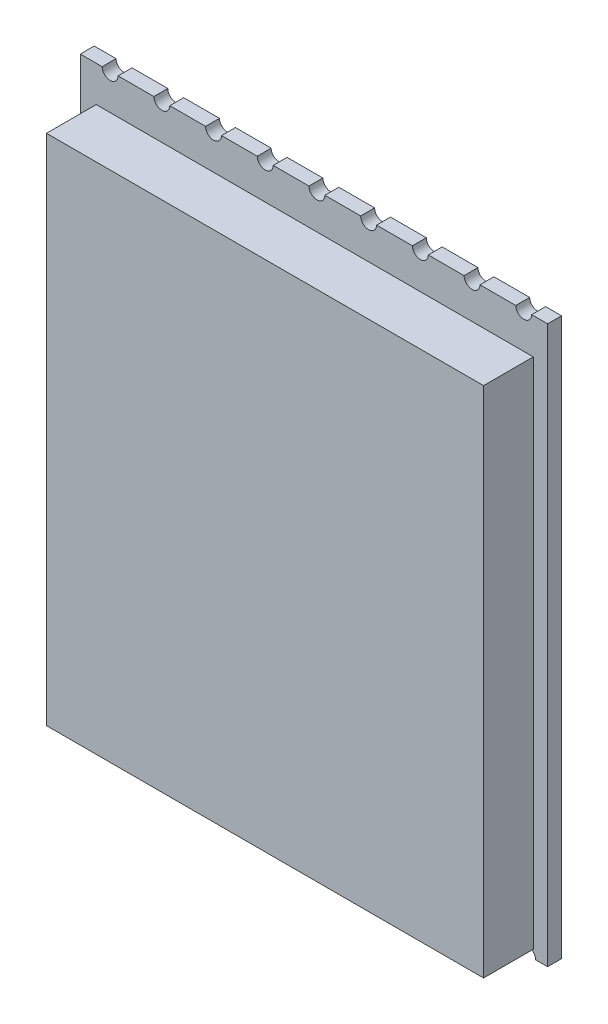
SolidWorks part; units mm, degrees
ref_plane "Front Plane" through (0, 0, 0) normal (0, 0, 1) x (1, 0, 0)
ref_plane "Top Plane" through (0, 0, 0) normal (0, 1, 0) x (1, 0, 0)
ref_plane "Right Plane" through (0, 0, 0) normal (1, 0, 0) x (0, 0, -1)
sketch "Sketch1" plane through (0, 0, 0) normal (0, 0, 1) x (1, 0, 0)
  line L1 (0, 0) -> (23.5, 0)
  line L2 (0, 0) -> (0, 28)
  line L3 (0, 28) -> (23.5, 28)
  line L4 (23.5, 0) -> (23.5, 28)
  dimension "D1" = 28
  dimension "D2" = 23.5
extrude "Boss-Extrude1" add sketch "Sketch1" along normal blind 0.7
sketch "Sketch2" plane through (0, 0, 0.7) normal (0, 0, 1) x (1, 0, 0)
  line L0 (0, 0) -> (23.5, 0) construction
  line L1 (0.8, 26.2) -> (22.78, 26.2)
  line L2 (0.8, 26.2) -> (0.8, 0.4)
  line L3 (0.8, 0.4) -> (22.78, 0.4)
  line L4 (22.78, 26.2) -> (22.78, 0.4)
  line L5 (23.5, 28) -> (0, 28) construction
  line L6 (0, 28) -> (0, 0) construction
  line L7 (23.5, 0) -> (23.5, 28) construction
  dimension "D1" = 21.98
  dimension "D2" = 25.8
  dimension "D3" = 0.4
  dimension "D4" = 1.8
  dimension "D5" = 0.8
  dimension "D6" = 0.72
extrude "Boss-Extrude2" add sketch "Sketch2" along normal blind 2.5
sketch "Sketch3" plane through (0, 0, 0.7) normal (0, 0, 1) x (1, 0, 0)
  line L0 (23.5, 28) -> (0, 28) construction
  line L1 (0, 28) -> (0, 0) construction
  line L3 (0, 0) -> (23.5, 0) construction
  line L4 (23.5, 0) -> (23.5, 28) construction
  circle A0 centre (1.5, 28) radius 0.4
  circle A1 centre (4.1, 28) radius 0.4
  circle A2 centre (6.7, 28) radius 0.4
  circle A3 centre (9.3, 28) radius 0.4
  circle A4 centre (11.9, 28) radius 0.4
  circle A5 centre (14.5, 28) radius 0.4
  circle A6 centre (17.1, 28) radius 0.4
  circle A7 centre (19.7, 28) radius 0.4
  circle A8 centre (22.3, 28) radius 0.4
  circle A9 centre (22.5, 0) radius 0.4
  circle A10 centre (19.9, 0) radius 0.4
  circle A11 centre (17.3, 0) radius 0.4
  dimension "D1" = 0.8
  dimension "D2" = 1.5
  dimension "D4" = 1
  dimension "D5" = 2.6
  dimension "D6" = 2.6
  dimension "D7" = 2.6
  dimension "D3" = 9
extrude "Cut-Extrude1" cut sketch "Sketch3" against normal blind 2.5
